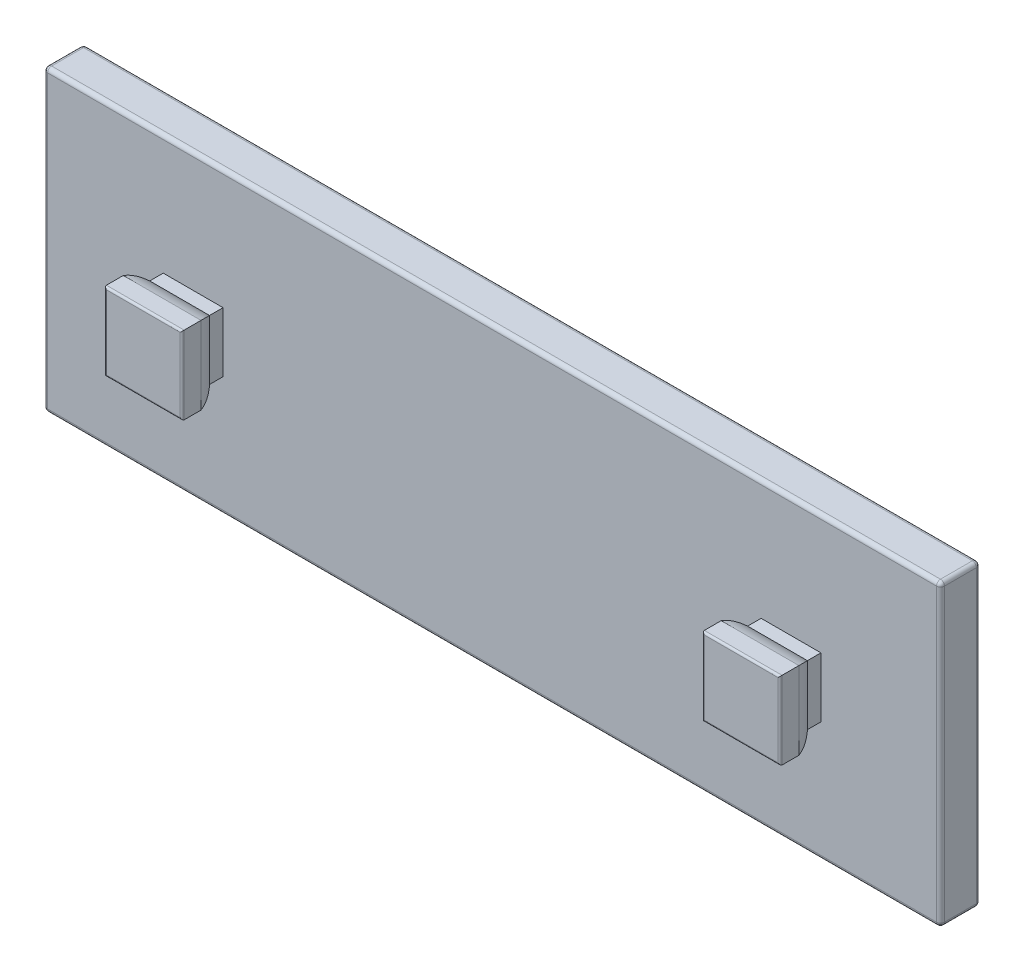
SolidWorks part; units mm, degrees
ref_plane "前视基准面" through (0, 0, 0) normal (0, 0, 1) x (1, 0, 0)
ref_plane "上视基准面" through (0, 0, 0) normal (0, 1, 0) x (1, 0, 0)
ref_plane "右视基准面" through (0, 0, 0) normal (1, 0, 0) x (0, 0, -1)
sketch "草图1" plane through (0, 0, 0) normal (0, 0, 1) x (1, 0, 0)
  line L1 (-22.5, -7.5) -> (22.5, -7.5)
  line L2 (-22.5, -7.5) -> (-22.5, 7.5)
  line L3 (-22.5, 7.5) -> (22.5, 7.5)
  line L4 (22.5, -7.5) -> (22.5, 7.5)
extrude "凸台-拉伸1" add sketch "草图1" against normal blind 2
sketch "草图2" plane through (0, 0, 0) normal (0, 0, 1) x (1, 0, 0)
  line L1 (-16.5, -1.5) -> (-13.5, -1.5)
  line L2 (-16.5, -1.5) -> (-16.5, 1.5)
  line L3 (-16.5, 1.5) -> (-13.5, 1.5)
  line L4 (-13.5, -1.5) -> (-13.5, 1.5)
  line L5 (13.5, 1.5) -> (16.5, 1.5)
  line L6 (13.5, 1.5) -> (13.5, -1.5)
  line L7 (13.5, -1.5) -> (16.5, -1.5)
  line L8 (16.5, 1.5) -> (16.5, -1.5)
extrude "凸台-拉伸2" add sketch "草图2" along normal blind 1
sketch "草图3" plane through (0, 0, 0) normal (0, 1, 0) x (1, 0, 0)
  line L0 (-16.95, -2.5) -> (-13.05, -2.5)
  line L1 (-16.95, -2.5) -> (-16.95, -1.5556)
  line L2 (-13.05, -2.5) -> (-13.05, -1.5556)
  line L3 (0, -3.2263) -> (0, 2.8368) construction
  line L4 (-16.5, -1) -> (-16.5, 0) construction
  line L5 (-16.5, -0.6771) -> (-13.5, -0.6771)
  line L6 (16.5, -0.6771) -> (13.5, -0.6771)
  line L7 (13.05, -2.5) -> (13.05, -1.5556)
  line L8 (16.95, -2.5) -> (16.95, -1.5556)
  line L9 (16.95, -2.5) -> (13.05, -2.5)
  arc A0 (-16.5, -0.6771) -> (-16.95, -1.5556) centre (-15, -2) ccw
  arc A1 (13.05, -1.5556) -> (13.5, -0.6771) centre (15, -2) cw
  arc A2 (-13.05, -1.5556) -> (-13.5, -0.6771) centre (-15, -2) ccw
  arc A3 (16.5, -0.6771) -> (16.95, -1.5556) centre (15, -2) cw
extrude "凸台-拉伸3" add sketch "草图3" along normal blind 2 and the other way blind 2
sketch "草图4" plane through (-16.95, 0, 0) normal (-1, 0, 0) x (0, 0, 1)
  line L0 (2.5, 1.95) -> (1.5556, 1.95)
  line L1 (0.6771, -2) -> (2.5, -2)
  line L2 (0.6771, -2) -> (0.6771, -1.5)
  line L3 (0.6771, 2) -> (2.5, 2)
  line L4 (2.5, -2) -> (2.5, -1.95)
  line L5 (2.5, -1.95) -> (1.5556, -1.95)
  line L7 (2.5, 1.95) -> (2.5, 2)
  line L8 (0.6771, 1.5) -> (0.6771, 2)
  arc A0 (1.5556, 1.95) -> (0.6771, 1.5) centre (2, 0) ccw
  arc A1 (0.6771, -1.5) -> (1.5556, -1.95) centre (2, 0) ccw
extrude "切除-拉伸1" cut sketch "草图4" against normal through all
fillet "圆角1" radius 0.2 12 edges at (0, -7.5, -2) (0, -7.5, 0) (-22.5, -7.5, -1) (-22.5, 0, -2) (-22.5, 0, 0) (-22.5, 7.5, -1) (0, 7.5, -2) (0, 7.5, 0) (22.5, 7.5, -1) (22.5, 0, -2) (22.5, -7.5, -1) (22.5, 0, 0)
fillet "圆角2" radius 0.1 8 edges at (13.05, 0, 2.5) (15, 1.95, 2.5) (16.95, 0, 2.5) (15, -1.95, 2.5) (-16.95, 0, 2.5) (-15, 1.95, 2.5) (-13.05, 0, 2.5) (-15, -1.95, 2.5)
